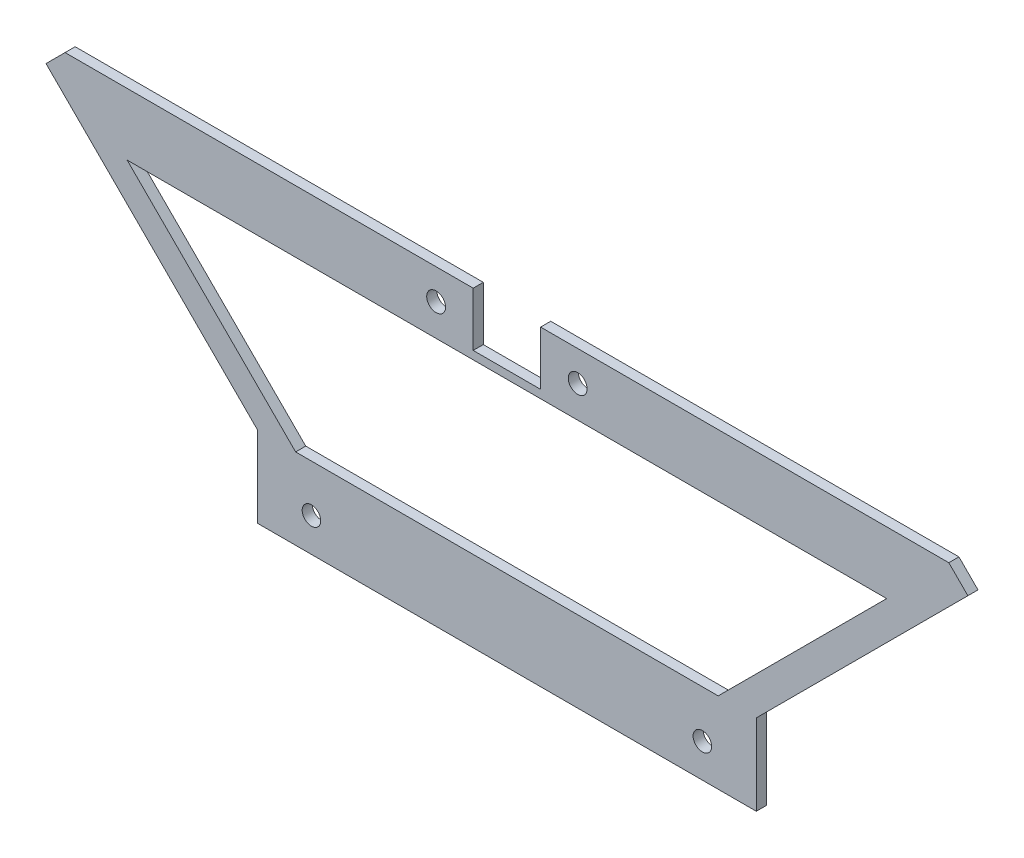
SolidWorks part; units mm, degrees
ref_plane "Front Plane" through (0, 0, 0) normal (0, 0, 1) x (1, 0, 0)
ref_plane "Top Plane" through (0, 0, 0) normal (0, 1, 0) x (1, 0, 0)
ref_plane "Right Plane" through (0, 0, 0) normal (1, 0, 0) x (0, 0, -1)
sketch "Sketch1" plane through (0, 0, 0) normal (0, 0, 1) x (1, 0, 0)
  line L0 (-37, 0) -> (37, 0)
  line L2 (68.3909, 43.3909) -> (65.5624, 46.2193)
  line L4 (-68.3801, 43.3801) -> (-65.5517, 46.2086)
  line L5 (-65.5517, 46.2086) -> (-31.3431, 12)
  line L6 (65.5624, 46.2193) -> (31.3431, 12)
  line L7 (31.3431, 12) -> (-31.3431, 12)
  line L8 (-68.3801, 43.3801) -> (-37, 12)
  line L9 (-37, 12) -> (-37, 0)
  line L10 (68.3909, 43.3909) -> (37, 12)
  line L11 (37, 12) -> (37, 0)
  line L12 (-65.5517, 46.2086) -> (65.5624, 46.2193)
  line L13 (-56.3431, 37) -> (56.3431, 37)
  line L14 (-5, 46.2135) -> (-5, 38.2135)
  line L15 (-5, 38.2135) -> (5, 38.2135)
  line L16 (5, 38.2135) -> (5, 46.2143)
  circle A0 centre (-29, 5) radius 1.375
  circle A1 centre (29, 5) radius 1.375
  circle A2 centre (-10.5, 41.7131) radius 1.4
  circle A3 centre (10.5, 41.7148) radius 1.4
  point P13 (-66.9659, 44.7943)
  dimension "D1" = 2.75
  dimension "D2" = 2.75
  dimension "D20" = 2.8
  dimension "D21" = 2.8
  dimension "D3" = 7
  dimension "D4" = 12
  dimension "D5" = 7
  dimension "D6" = 58
  dimension "D7" = 74
  dimension "D8" = 29
  dimension "D9" = 37
  dimension "D10" = 55
  dimension "D11" = 55
  dimension "D12" = 4
  dimension "D13" = 4
  dimension "D14" = 135
  dimension "D15" = 135
  dimension "D16" = 12
  dimension "D17" = 12
  dimension "D18" = 25
  dimension "D19" = 21
  dimension "D22" = 10.5
  dimension "D23" = 4.5
  dimension "D24" = 8
  dimension "D25" = 10
  dimension "D26" = 5.5
  dimension "D27" = 4.5
extrude "Boss-Extrude1" add sketch "Sketch1" along normal blind 1.5 contours L11 L10 L2 L6 L7 L5 L4 L8 L9 L0 A1 A0 | L16 L15 L14 L12 L5 L13 L6 A3 A2
